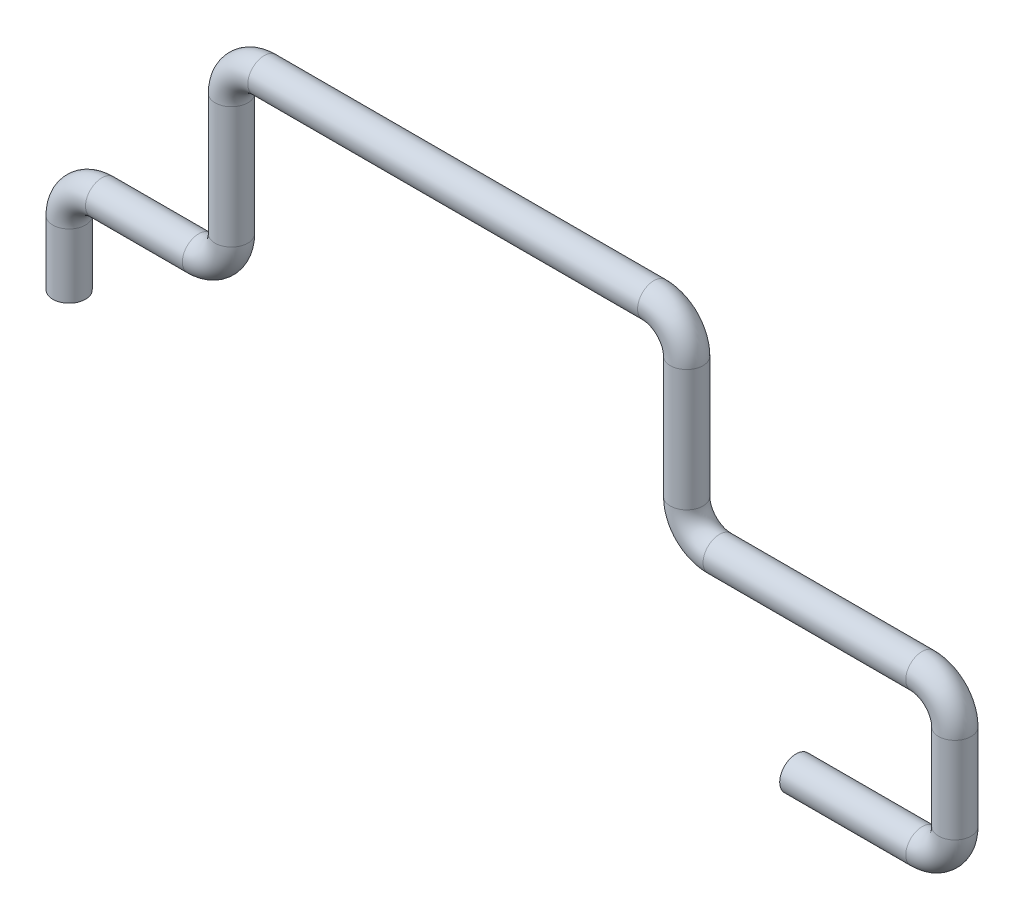
SolidWorks part; units mm, degrees
ref_plane "Front Plane" through (0, 0, 0) normal (0, 0, 1) x (1, 0, 0)
ref_plane "Top Plane" through (0, 0, 0) normal (0, 1, 0) x (1, 0, 0)
ref_plane "Right Plane" through (0, 0, 0) normal (1, 0, 0) x (0, 0, -1)
sketch "Croquis1" plane through (0, 0, 0) normal (0, 0, 1) x (1, 0, 0)
  line L0 (0, 0) -> (0, 9.8201)
  line L1 (5, 14.8201) -> (19.79, 14.8201)
  line L2 (24.79, 19.8201) -> (24.79, 38.3824)
  line L3 (29.79, 43.3824) -> (89.3097, 43.3824)
  line L4 (94.3097, 38.3824) -> (94.3097, 19.8201)
  line L5 (99.3097, 14.8201) -> (130.267, 14.8201)
  line L6 (135.267, 9.8201) -> (135.267, -3.3531)
  line L7 (130.267, -8.3531) -> (111.0159, -8.3531)
  line L9 (-3.4756, 0) -> (-3.4756, 14.8201) construction
  arc A0 (135.267, -3.3531) -> (130.267, -8.3531) centre (130.267, -3.3531) cw
  arc A1 (130.267, 14.8201) -> (135.267, 9.8201) centre (130.267, 9.8201) cw
  arc A2 (94.3097, 19.8201) -> (99.3097, 14.8201) centre (99.3097, 19.8201) ccw
  arc A3 (89.3097, 43.3824) -> (94.3097, 38.3824) centre (89.3097, 38.3824) cw
  arc A4 (24.79, 38.3824) -> (29.79, 43.3824) centre (29.79, 38.3824) cw
  arc A5 (19.79, 14.8201) -> (24.79, 19.8201) centre (19.79, 19.8201) ccw
  arc A6 (0, 9.8201) -> (5, 14.8201) centre (5, 9.8201) cw
  dimension "D2" = 5
  dimension "D1" = 6.9512
sweep "Barrer4" add path "Croquis1" circular profile diameter 5 parameters "D3"=5
shell "Vaciado2" thickness 0.01
